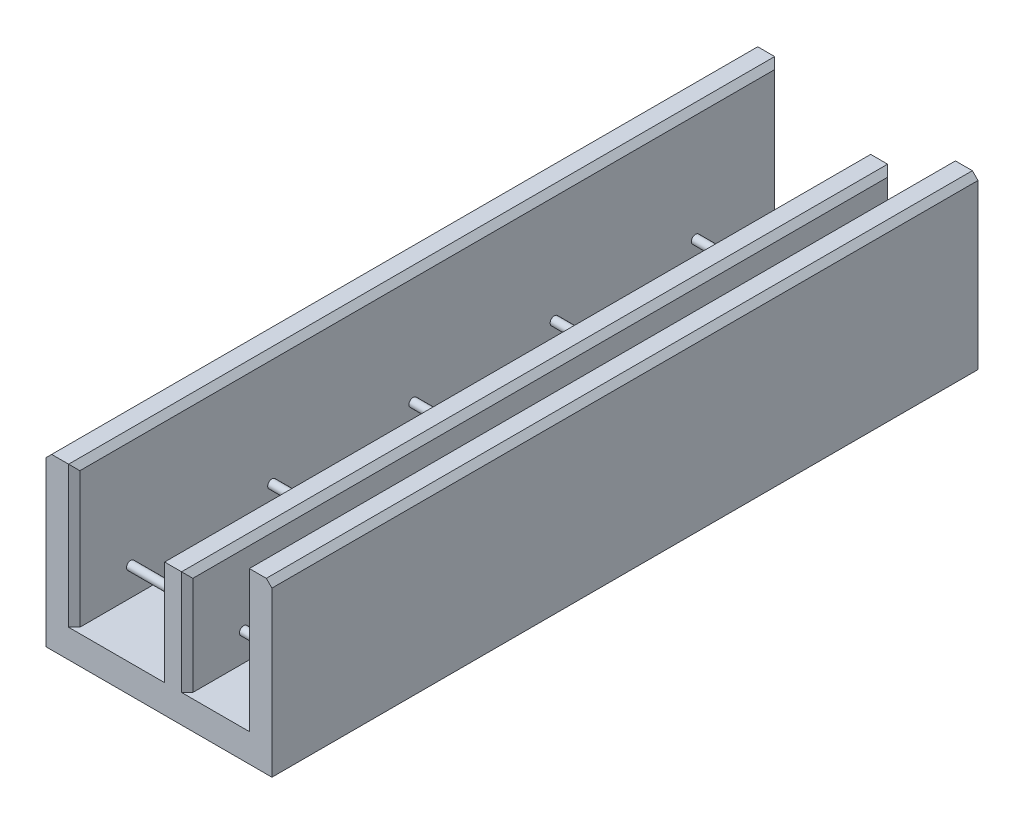
SolidWorks part; units mm, degrees
ref_plane "Alzado" through (0, 0, 0) normal (0, 0, 1) x (1, 0, 0)
ref_plane "Planta" through (0, 0, 0) normal (0, 1, 0) x (1, 0, 0)
ref_plane "Vista lateral" through (0, 0, 0) normal (1, 0, 0) x (0, 0, -1)
sketch "Croquis1" plane through (0, 0, 0) normal (0, 0, 1) x (1, 0, 0)
  line L0 (0, 0) -> (-800, 0)
  line L1 (-800, 0) -> (-800, 600)
  line L2 (-800, 600) -> (-700, 600)
  line L3 (-700, 600) -> (-700, 100)
  line L4 (-700, 100) -> (-400, 100)
  line L5 (-400, 100) -> (-400, 470)
  line L6 (-400, 470) -> (-300, 470)
  line L7 (-300, 470) -> (-300, 100)
  line L8 (-300, 100) -> (-100, 100)
  line L9 (-100, 100) -> (-100, 600)
  line L10 (-100, 600) -> (0, 600)
  line L11 (0, 600) -> (0, 0)
  dimension "D1" = 800
  dimension "D2" = 600
  dimension "D3" = 100
  dimension "D4" = 500
  dimension "D5" = 300
  dimension "D6" = 370
  dimension "D7" = 100
  dimension "D8" = 370
  dimension "D9" = 200
extrude "Saliente-Extruir1" add sketch "Croquis1" along normal blind 2500
chamfer "Chaflán2" distance 20 angle 45 14 edges at (-100, 350, 0) (0, 600, 1250) (-700, 350, 0) (-700, 600, 1250) (-700, 350, 2500) (-100, 350, 2500) (-300, 285, 0) (-300, 285, 2500) (-300, 470, 1250) (-400, 285, 0) (-400, 285, 2500) (-400, 470, 1250) (-800, 600, 1250) (-100, 600, 1250)
sketch "Croquis2" plane through (-800, 0, 0) normal (-1, 0, 0) x (0, 0, 1)
  line L0 (0, 580) -> (0, 0) construction
  circle A0 centre (300, 200) radius 15
  dimension "D3" = 30
  dimension "D1" = 300
extrude "Saliente-Extruir2" add sketch "Croquis2" against normal up to surface (700 mm away) up to face at (-100, 340, 1250)
pattern_linear "MatrizL1" count 5 spacing 500 along (0, 0, 1) of "Saliente-Extruir2"
